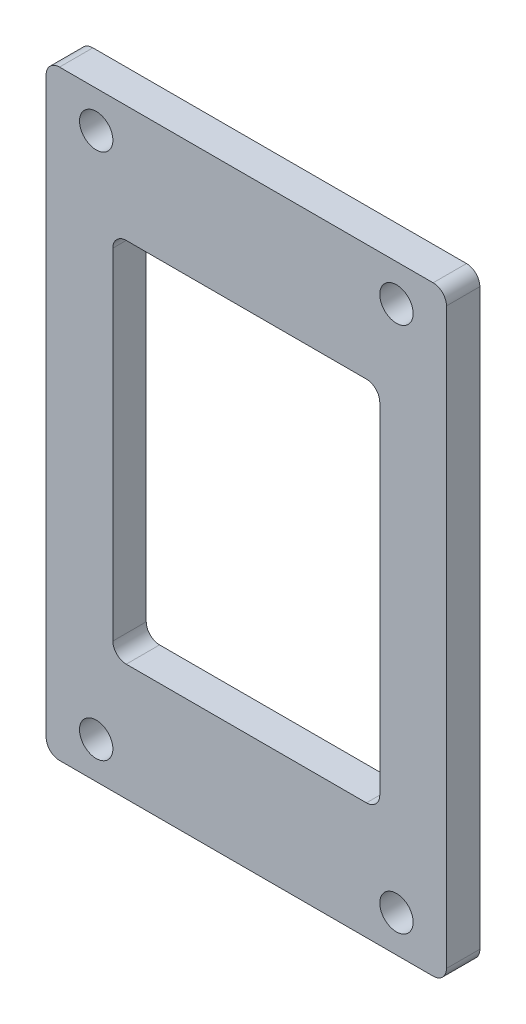
SolidWorks part; units mm, degrees
ref_plane "Plan de face" through (0, 0, 0) normal (0, 0, 1) x (1, 0, 0)
ref_plane "Plan de dessus" through (0, 0, 0) normal (0, 1, 0) x (1, 0, 0)
ref_plane "Plan de droite" through (0, 0, 0) normal (1, 0, 0) x (0, 0, -1)
sketch "Esquisse1" plane through (0, 0, 0) normal (0, 0, 1) x (1, 0, 0)
  line L1 (28, -45) -> (-28, -45)
  line L2 (30, -43) -> (30, 43)
  line L3 (28, 45) -> (-28, 45)
  line L4 (-30, -43) -> (-30, 43)
  line L5 (30, -45) -> (-30, 45) construction
  line L6 (30, 45) -> (-30, -45) construction
  arc A0 (-28, -45) -> (-30, -43) centre (-28, -43) cw
  arc A1 (28, -45) -> (30, -43) centre (28, -43) ccw
  arc A2 (30, 43) -> (28, 45) centre (28, 43) ccw
  arc A3 (-28, 45) -> (-30, 43) centre (-28, 43) ccw
  point P0 (0, 0)
  dimension "D3" = 2
  dimension "D1" = 60
  dimension "D2" = 90
extrude "Boss.-Extru.1" add sketch "Esquisse1" along normal blind 5
sketch "Esquisse2" plane through (0, 0, 0) normal (0, 0, -1) x (-1, 0, 0)
  line L1 (18, -27.5) -> (-18, -27.5)
  line L2 (20, -25.5) -> (20, 25.5)
  line L3 (18, 27.5) -> (-18, 27.5)
  line L4 (-20, -25.5) -> (-20, 25.5)
  line L5 (20, -27.5) -> (-20, 27.5) construction
  line L6 (20, 27.5) -> (-20, -27.5) construction
  arc A0 (-18, -27.5) -> (-20, -25.5) centre (-18, -25.5) cw
  arc A1 (18, -27.5) -> (20, -25.5) centre (18, -25.5) ccw
  arc A2 (20, 25.5) -> (18, 27.5) centre (18, 25.5) ccw
  arc A3 (-18, 27.5) -> (-20, 25.5) centre (-18, 25.5) ccw
  point P0 (0, 0)
  dimension "D3" = 2
  dimension "D1" = 55
  dimension "D2" = 40
extrude "Enlèv. mat.-Extru.1" cut sketch "Esquisse2" against normal through all
sketch "Esquisse3" plane through (0, 0, 5) normal (0, 0, 1) x (1, 0, 0)
  line L0 (28, 45) -> (-28, 45) construction
  line L1 (30, -43) -> (30, 43) construction
  line L2 (-28, -45) -> (28, -45) construction
  line L3 (-30, 43) -> (-30, -43) construction
  circle A4 centre (-22.5, -39.5) radius 2.5
  circle A5 centre (22.5, -39.5) radius 2.5
  circle A6 centre (-22.5, 39.5) radius 2.5
  circle A7 centre (22.5, 39.5) radius 2.5
  point P1 (0, 0)
  point P15 (0, 0)
  point P16 (0, 0)
  point P17 (0, 0)
  point P18 (0, 0)
  point P19 (-24.495, 39.5)
  dimension "D3" = 5
  dimension "D4" = 5
  dimension "D5" = 5
  dimension "D7" = 5
  dimension "D1" = 5.5
  dimension "D2" = 7.5
  dimension "D6" = 5.5
  dimension "D8" = 7.5
extrude "Enlèv. mat.-Extru.2" cut sketch "Esquisse3" against normal through all
